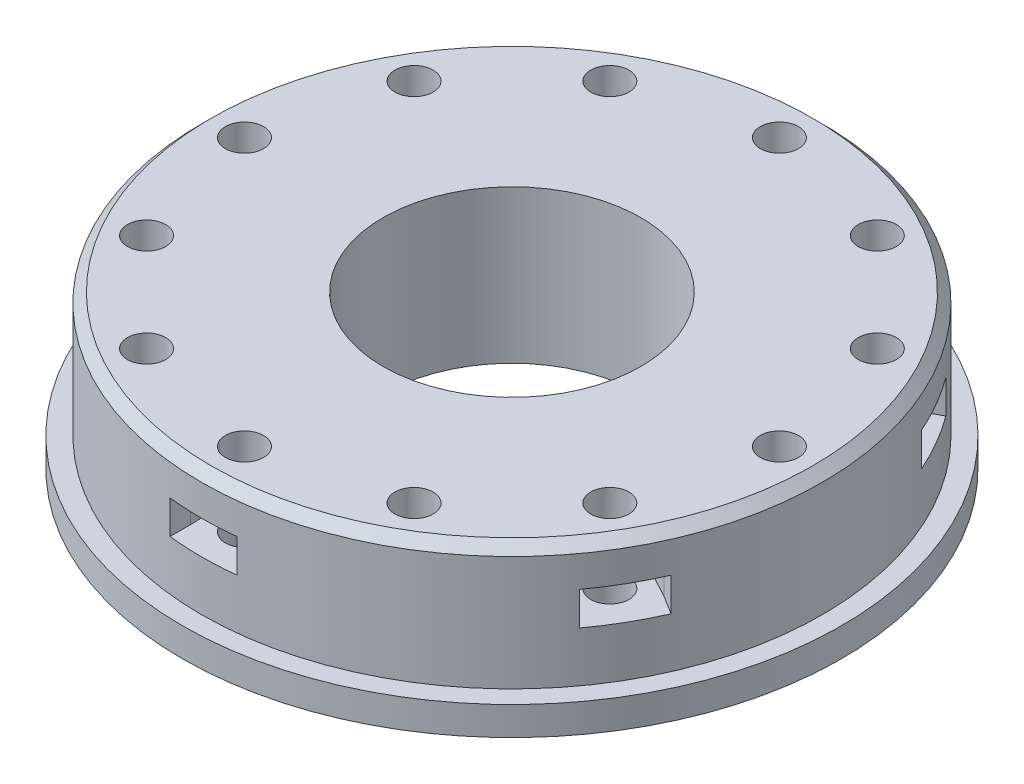
SolidWorks part; units mm, degrees
material "尼龙 101"
ref_plane "前视基准面" through (0, 0, 0) normal (0, 0, 1) x (1, 0, 0)
ref_plane "上视基准面" through (0, 0, 0) normal (0, 1, 0) x (1, 0, 0)
ref_plane "右视基准面" through (0, 0, 0) normal (1, 0, 0) x (0, 0, -1)
sketch "草图1" plane through (0, 0, 0) normal (0, 1, 0) x (1, 0, 0)
  circle A0 centre (0, 0) radius 34.5
  dimension "D1" = 69
extrude "凸台-拉伸1" add sketch "草图1" along normal blind 16
sketch "草图2" plane through (0, 16, 0) normal (0, 1, 0) x (1, 0, 0)
  circle A0 centre (0, 0) radius 32.5
  circle A1 centre (0, 0) radius 34.5 construction
  circle A2 centre (0, 0) radius 34.5
  dimension "D1" = 65
extrude "切除-拉伸1" cut sketch "草图2" against normal blind 13
sketch "草图3" plane through (0, 16, 0) normal (0, 1, 0) x (1, 0, 0)
  circle A0 centre (0, 0) radius 28 construction
  circle A1 centre (-28, 0) radius 2
  circle A11 centre (-14, 24.2487) radius 2
  circle A12 centre (14, 24.2487) radius 2
  circle A13 centre (28, 0) radius 2
  circle A14 centre (14, -24.2487) radius 2
  circle A15 centre (-14, -24.2487) radius 2
  dimension "D1" = 56
  dimension "D2" = 4
  dimension "D3" = 6
extrude "切除-拉伸3" cut sketch "草图3" against normal through all contours A0 A1 | A0 A1 | A0 A11 | A0 A11 | A15
sketch "草图7" plane through (0, 16, 0) normal (0, 1, 0) x (1, 0, 0)
  circle A0 centre (0, 0) radius 13.5
  dimension "D1" = 27
extrude "切除-拉伸6" cut sketch "草图7" against normal through all
sketch "草图8" plane through (0, 0, 0) normal (0, -1, 0) x (1, 0, 0)
  line L0 (14.841, -20.2367) -> (10.946, -21.5144)
  line L1 (31.895, 1.2776) -> (28.841, 4.012)
  line L2 (28.841, 4.012) -> (24.946, 2.7344)
  line L3 (24.946, 2.7344) -> (24.105, -1.2776)
  line L4 (24.105, -1.2776) -> (27.159, -4.012)
  line L5 (27.159, -4.012) -> (31.054, -2.7344)
  line L6 (31.054, -2.7344) -> (31.895, 1.2776)
  line L7 (10.946, -21.5144) -> (10.105, -25.5263)
  line L8 (10.105, -25.5263) -> (13.159, -28.2607)
  line L9 (13.159, -28.2607) -> (17.054, -26.9831)
  line L10 (17.054, -26.9831) -> (17.895, -22.9711)
  line L11 (17.895, -22.9711) -> (14.841, -20.2367)
  line L12 (-10.105, -22.9711) -> (-13.159, -20.2367)
  line L13 (-13.159, -20.2367) -> (-17.054, -21.5144)
  line L14 (-17.054, -21.5144) -> (-17.895, -25.5263)
  line L15 (-17.895, -25.5263) -> (-14.841, -28.2607)
  line L16 (-14.841, -28.2607) -> (-10.946, -26.9831)
  line L17 (-10.946, -26.9831) -> (-10.105, -22.9711)
  line L18 (-24.946, -2.7344) -> (-24.105, 1.2776)
  line L19 (-24.105, 1.2776) -> (-27.159, 4.012)
  line L20 (-27.159, 4.012) -> (-31.054, 2.7344)
  line L21 (-31.054, 2.7344) -> (-31.895, -1.2776)
  line L22 (-31.895, -1.2776) -> (-28.841, -4.012)
  line L23 (-28.841, -4.012) -> (-24.946, -2.7344)
  line L24 (-14.841, 20.2367) -> (-10.946, 21.5144)
  line L25 (-10.946, 21.5144) -> (-10.105, 25.5263)
  line L26 (-10.105, 25.5263) -> (-13.159, 28.2607)
  line L27 (-13.159, 28.2607) -> (-17.054, 26.9831)
  line L28 (-17.054, 26.9831) -> (-17.895, 22.9711)
  line L29 (-17.895, 22.9711) -> (-14.841, 20.2367)
  line L30 (10.105, 22.9711) -> (13.159, 20.2367)
  line L31 (13.159, 20.2367) -> (17.054, 21.5144)
  line L32 (17.054, 21.5144) -> (17.895, 25.5263)
  line L33 (17.895, 25.5263) -> (14.841, 28.2607)
  line L34 (14.841, 28.2607) -> (10.946, 26.9831)
  line L35 (10.946, 26.9831) -> (10.105, 22.9711)
  circle A11 centre (28, 0) radius 3.55 construction
  point P1 (26.8935, 3.3732)
  dimension "D1" = 7.1
extrude "切除-拉伸7" cut sketch "草图8" against normal blind 8
chamfer "倒角4" distance 1 angle 45 1 edges at (0, 16, 32.5)
ref_plane "基准面1" through (0, 10, 0) normal (0, 1, 0) x (1, 0, 0)
sketch "草图10" plane through (0, 10, 0) normal (0, 1, 0) x (1, 0, 0)
  line L6 (-3.4824, -30.1625) -> (-3.614, -26.0654)
  line L9 (3.4824, -25.8375) -> (3.614, -29.9346)
  line L10 (-0.1316, -23.9029) -> (3.4824, -25.8375)
  line L11 (-3.614, -26.0654) -> (-0.1316, -23.9029)
  line L36 (-3.4824, -30.1625) -> (-3.4824, -34.3238)
  line L37 (-3.4824, -34.3238) -> (3.4824, -34.3238)
  line L38 (3.4824, -34.3238) -> (3.614, -29.9346)
  line L39 (-27.8627, -12.0654) -> (-24.3803, -9.9029)
  line L40 (-20.6347, -15.9346) -> (-24.1171, -18.0971)
  line L41 (-20.7663, -11.8375) -> (-20.6347, -15.9346)
  line L42 (-24.3803, -9.9029) -> (-20.7663, -11.8375)
  line L43 (-27.8627, -12.0654) -> (-31.4665, -14.1461)
  line L44 (-31.4665, -14.1461) -> (-27.9841, -20.1777)
  line L45 (-27.9841, -20.1777) -> (-24.1171, -18.0971)
  line L46 (-24.3803, 18.0971) -> (-20.7663, 16.1625)
  line L47 (-24.1171, 9.9029) -> (-27.7311, 11.8375)
  line L48 (-20.6347, 12.0654) -> (-24.1171, 9.9029)
  line L49 (-20.7663, 16.1625) -> (-20.6347, 12.0654)
  line L50 (-24.3803, 18.0971) -> (-27.9841, 20.1777)
  line L51 (-27.9841, 20.1777) -> (-31.4665, 14.1461)
  line L52 (-31.4665, 14.1461) -> (-27.7311, 11.8375)
  line L53 (3.4824, 30.1625) -> (3.614, 26.0654)
  line L54 (-3.4824, 25.8375) -> (-3.614, 29.9346)
  line L55 (0.1316, 23.9029) -> (-3.4824, 25.8375)
  line L56 (3.614, 26.0654) -> (0.1316, 23.9029)
  line L57 (3.4824, 30.1625) -> (3.4824, 34.3238)
  line L58 (3.4824, 34.3238) -> (-3.4824, 34.3238)
  line L59 (-3.4824, 34.3238) -> (-3.614, 29.9346)
  line L60 (27.8627, 12.0654) -> (24.3803, 9.9029)
  line L61 (20.6347, 15.9346) -> (24.1171, 18.0971)
  line L62 (20.7663, 11.8375) -> (20.6347, 15.9346)
  line L63 (24.3803, 9.9029) -> (20.7663, 11.8375)
  line L64 (27.8627, 12.0654) -> (31.4665, 14.1461)
  line L65 (31.4665, 14.1461) -> (27.9841, 20.1777)
  line L66 (27.9841, 20.1777) -> (24.1171, 18.0971)
  line L67 (24.3803, -18.0971) -> (20.7663, -16.1625)
  line L68 (24.1171, -9.9029) -> (27.7311, -11.8375)
  line L69 (20.6347, -12.0654) -> (24.1171, -9.9029)
  line L70 (20.7663, -16.1625) -> (20.6347, -12.0654)
  line L71 (24.3803, -18.0971) -> (27.9841, -20.1777)
  line L72 (27.9841, -20.1777) -> (31.4665, -14.1461)
  line L73 (31.4665, -14.1461) -> (27.7311, -11.8375)
  circle A0 centre (0, 0) radius 28 construction
  circle A1 centre (0, 0) radius 34.5 construction
  dimension "D2" = 4.0992
  dimension "D3" = 7.1
  dimension "D6" = 8.1984
  dimension "D1" = 6
extrude "切除-拉伸8" cut sketch "草图10" against normal mid plane 3.5
sketch "草图11" plane through (0, 0, 0) normal (0, -1, 0) x (1, 0, 0)
  circle A0 centre (0, 0) radius 28 construction
  circle A1 centre (0, 28) radius 2
  circle A2 centre (24.2487, 14) radius 2
  circle A3 centre (24.2487, -14) radius 2
  circle A4 centre (0, -28) radius 2
  circle A5 centre (-24.2487, -14) radius 2
  circle A6 centre (-24.2487, 14) radius 2
  dimension "D1" = 4
  dimension "D2" = 6
extrude "切除-拉伸9" cut sketch "草图11" against normal up to surface (16 mm away) up to face at (0, 16, 31.5)
